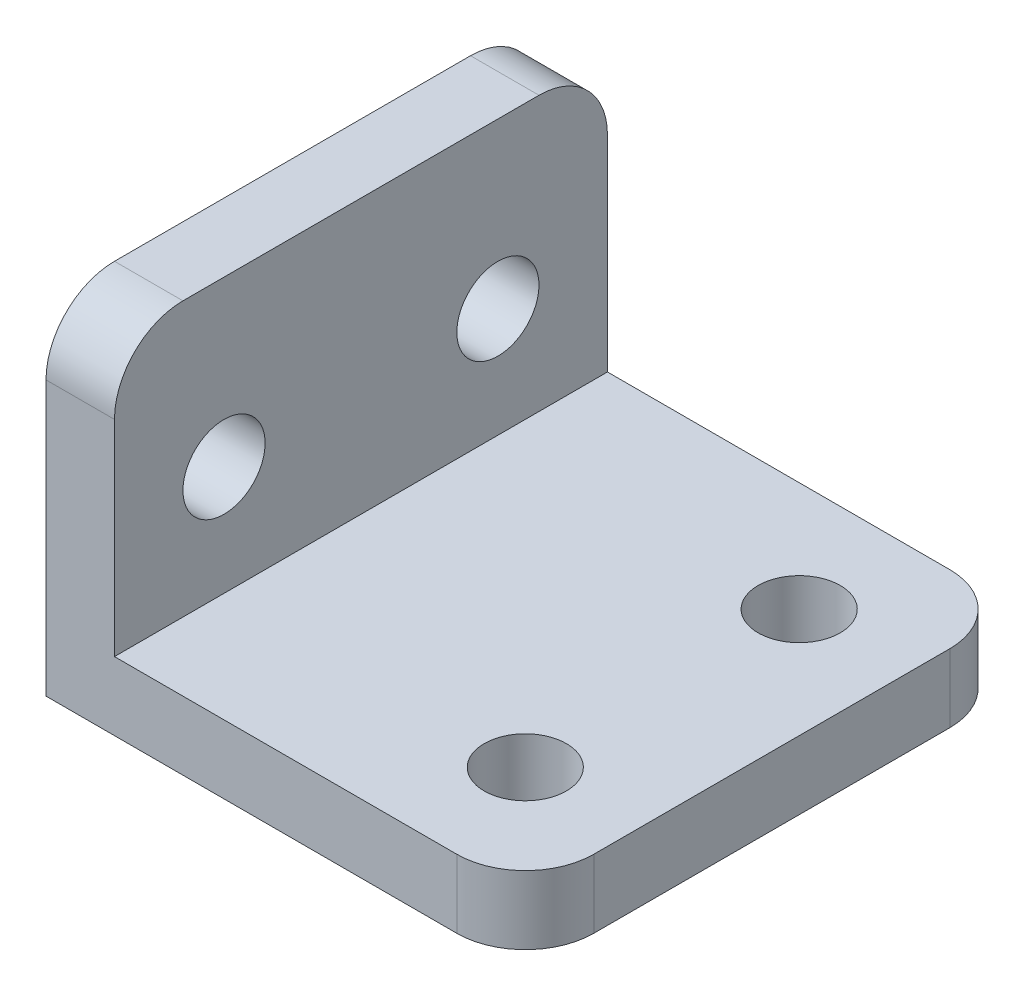
SolidWorks part; units mm, degrees
ref_plane "Front Plane" through (0, 0, 0) normal (0, 0, 1) x (1, 0, 0)
ref_plane "Top Plane" through (0, 0, 0) normal (0, 1, 0) x (1, 0, 0)
ref_plane "Right Plane" through (0, 0, 0) normal (1, 0, 0) x (0, 0, -1)
sketch "Sketch1" plane through (0, 0, 0) normal (0, 0, 1) x (1, 0, 0)
  line L0 (0, 19.0955) -> (0, -0.9045)
  line L1 (0, -0.9045) -> (30, -0.9045)
  line L2 (30, -0.9045) -> (30, -5.9045)
  line L3 (30, -5.9045) -> (-5, -5.9045)
  line L4 (-5, -5.9045) -> (-5, 19.0955)
  line L5 (-5, 19.0955) -> (0, 19.0955)
  dimension "D1" = 25
  dimension "D2" = 5
  dimension "D3" = 5
  dimension "D4" = 35
extrude "Boss-Extrude1" add sketch "Sketch1" along normal blind 36
sketch "Sketch2" plane through (0, -0.9045, 0) normal (0, 1, 0) x (1, 0, 0)
  line L2 (0, -36) -> (0, 0) construction
  line L4 (30, -36) -> (0, -36) construction
  circle A0 centre (22, -8) radius 3
  circle A1 centre (22, -28) radius 3
  dimension "D1" = 6
  dimension "D2" = 6
  dimension "D3" = 20
  dimension "D4" = 8
  dimension "D5" = 22
extrude "Cut-Extrude1" cut sketch "Sketch2" against normal blind 5
sketch "Sketch3" plane through (0, 0, 0) normal (1, 0, 0) x (0, 0, -1)
  line L0 (0, -0.9045) -> (0, 19.0955) construction
  line L1 (-36, -0.9045) -> (-36, 19.0955) construction
  line L2 (-36, 19.0955) -> (0, 19.0955) construction
  circle A0 centre (-28, 7.0955) radius 3
  circle A1 centre (-8, 7.0955) radius 3
  dimension "D1" = 6
  dimension "D2" = 6
  dimension "D3" = 8
  dimension "D4" = 8
  dimension "D5" = 12
  dimension "D6" = 12
extrude "Cut-Extrude2" cut sketch "Sketch3" against normal blind 5
fillet "Fillet1" radius 5 4 edges at (30, -3.4045, 36) (30, -3.4045, 0) (-2.5, 19.0955, 0) (-2.5, 19.0955, 36)
